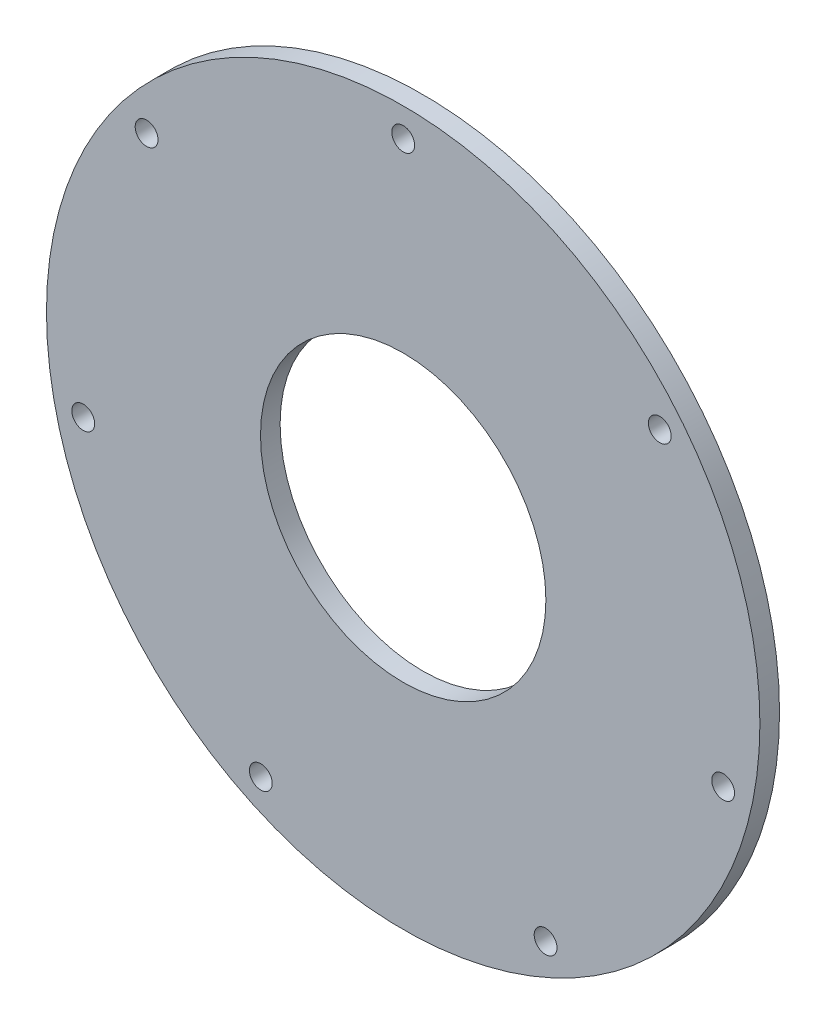
SolidWorks part; units mm, degrees
ref_plane "Ebene vorne" through (0, 0, 0) normal (0, 0, 1) x (1, 0, 0)
ref_plane "Ebene oben" through (0, 0, 0) normal (0, 1, 0) x (1, 0, 0)
ref_plane "Ebene rechts" through (0, 0, 0) normal (1, 0, 0) x (0, 0, -1)
sketch "Skizze1" plane through (0, 0, 0) normal (0, 0, 1) x (1, 0, 0)
  circle A0 centre (0, 0) radius 50
  circle A1 centre (0, 0) radius 20
  dimension "D1" = 100
  dimension "D2" = 40
extrude "Aufsatz-Linear austragen1" add sketch "Skizze1" along normal blind 2.75
hole_wizard "Ø3.2 (3.2) Durchmesser Bohrung1" positions "Skizze2" profile "Skizze3" hole size "Ø3.2" standard "ISO" end condition through all
sketch "Skizze2" plane through (0, 0, 2.75) normal (0, 0, 1) x (1, 0, 0)
  line L0 (0, 0) -> (0, -50000) construction
  circle A0 centre (0, 0) radius 46 construction
  circle A1 centre (0.0005, 0.0009) radius 46 construction
  circle A2 centre (0, 0.0017) radius 46 construction
  circle A3 centre (-0.001, 0.0017) radius 46 construction
  circle A4 centre (-0.0015, 0.0009) radius 46 construction
  circle A5 centre (-0.001, 0) radius 46 construction
  point P8 (0, 46)
  dimension "D1" = 92
  dimension "D2" = 6
sketch "Skizze3" plane through (0, 46, 2.75) normal (1, 0, 0) x (0, -1, 0)
  line L0 (0, 0) -> (0, 2.75)
  line L1 (0, 2.75) -> (1.6, 2.75)
  line L2 (1.6, 2.75) -> (1.6, 0)
  line L5 (1.6, 0) -> (0, 0)
  line L11 (0, -6.35) -> (0, 107.95) construction
  dimension "Bohrerdurchmesser" = 3.2
  dimension "Bohrungstiefe" = 2.75
pattern_circular "Kreismuster1" count 7 over 360 about axis through (0, 0, 0) along (0, 0, 1) of "Ø3.2 (3.2) Durchmesser Bohrung1"
